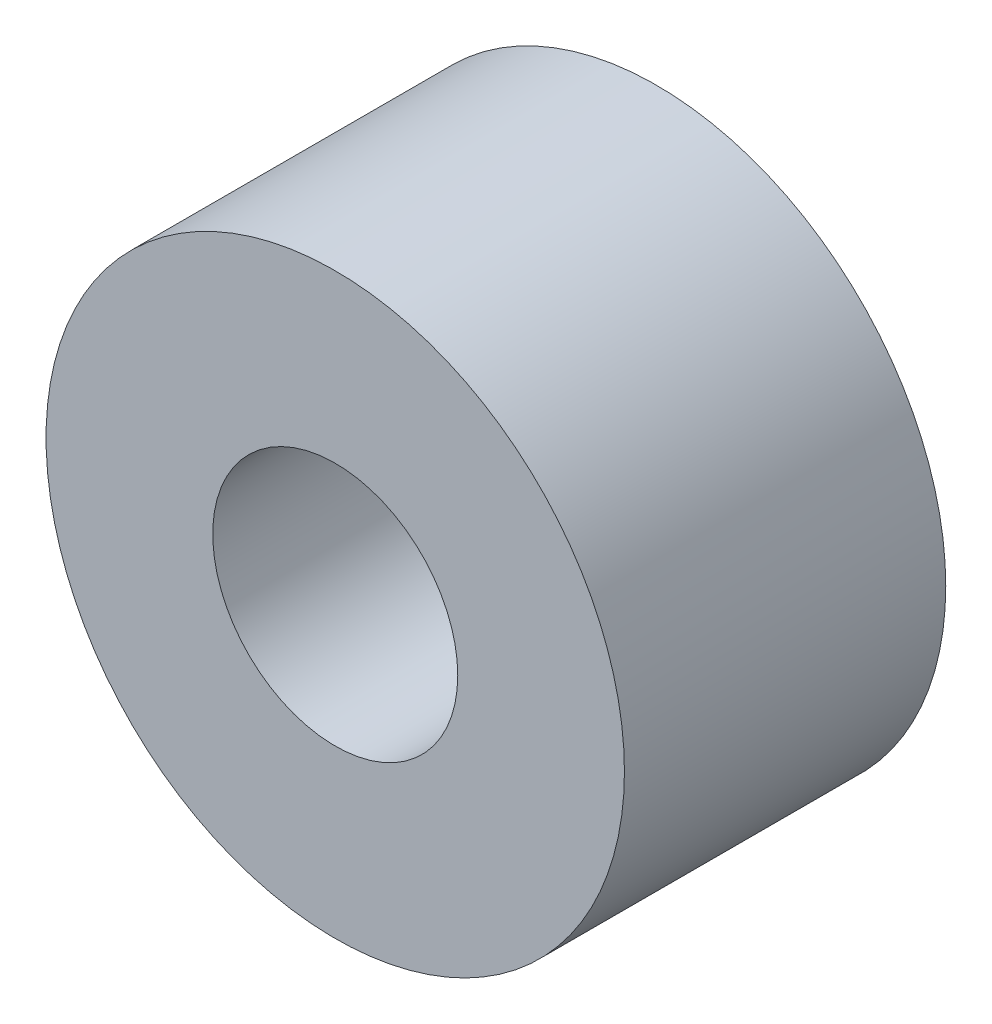
SolidWorks part; units mm, degrees
ref_plane "前视基准面" through (0, 0, 0) normal (0, 0, 1) x (1, 0, 0)
ref_plane "上视基准面" through (0, 0, 0) normal (0, 1, 0) x (1, 0, 0)
ref_plane "右视基准面" through (0, 0, 0) normal (1, 0, 0) x (0, 0, -1)
other "Configuration Table"
sketch "草图1" plane through (0, 0, 0) normal (0, 0, 1) x (1, 0, 0)
  circle A0 centre (0, 0) radius 3.6
  circle A1 centre (0, 0) radius 1.525
  dimension "D1" = 7.2
  dimension "D2" = 3.05
extrude "凸台-拉伸1" add sketch "草图1" along normal blind 4
